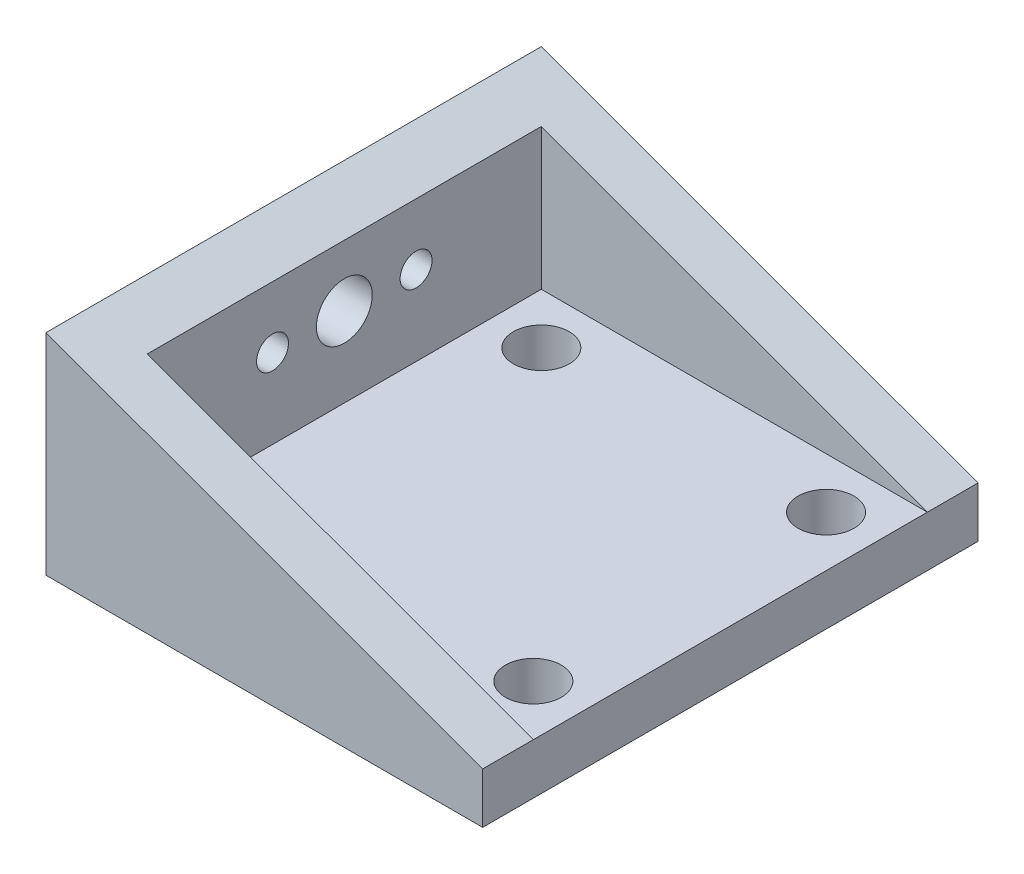
SolidWorks part; units mm, degrees
ref_plane "Front Plane" through (0, 0, 0) normal (0, 0, 1) x (1, 0, 0)
ref_plane "Top Plane" through (0, 0, 0) normal (0, 1, 0) x (1, 0, 0)
ref_plane "Right Plane" through (0, 0, 0) normal (1, 0, 0) x (0, 0, -1)
sketch "Sketch1" plane through (0, 0, 0) normal (0, 0, 1) x (1, 0, 0)
  line L0 (0, 0) -> (0, 13.175)
  line L1 (0, 13.175) -> (27.375, 3.175)
  line L2 (0, 0) -> (27.375, 0)
  line L5 (27.375, 3.175) -> (27.375, 0)
  point P2 (31.75, 0)
  point P3 (3.175, 0)
  dimension "D1" = 13.175
  dimension "D3" = 3.175
  dimension "D4" = 24.2
  dimension "D5" = 4.375
  dimension "D6" = 3.175
extrude "Boss-Extrude1" add sketch "Sketch1" along normal mid plane 31.05
sketch "Sketch2" plane through (0, 0, 0) normal (0, -1, 0) x (1, 0, 0)
  line L0 (27.375, 15.525) -> (27.375, -15.525) construction
  line L1 (3.175, 12.35) -> (27.375, 12.35)
  line L2 (3.175, 12.35) -> (3.175, -12.35)
  line L3 (3.175, -12.35) -> (27.375, -12.35)
  line L4 (27.375, 12.35) -> (27.375, -12.35)
  line L5 (0, 15.525) -> (27.375, 15.525) construction
  line L7 (27.375, 15.525) -> (27.375, 12.35) construction
  line L8 (27.375, -12.35) -> (27.375, -15.525) construction
  dimension "D1" = 3.175
extrude "Cut-Extrude1" cut sketch "Sketch2" against normal up to next from offset 3.175 offset against normal yes
sketch "Sketch4" plane through (0, 0, 0) normal (1, 0, 0) x (0, 0, -1)
  line L0 (0, 0) -> (0, 13.175) construction
  line L1 (4.5, 8.175) -> (-4.5, 8.175) construction
  circle A0 centre (0, 8.175) radius 1.75
  circle A1 centre (-4.5, 8.175) radius 1
  circle A2 centre (4.5, 8.175) radius 1
  dimension "D2" = 3.5
  dimension "D4" = 2
  dimension "D5" = 2
  dimension "D1" = 8.175
  dimension "D3" = 4.5
extrude "Cut-Extrude2" cut sketch "Sketch4" along normal up to next
sketch "Sketch5" plane through (0, 0, 0) normal (0, 1, 0) x (1, 0, 0)
  line L0 (3.175, -12.35) -> (27.375, -12.35) construction
  line L1 (3.175, -12.35) -> (3.175, 12.35) construction
  line L2 (3.175, 12.35) -> (27.375, 12.35) construction
  line L3 (27.375, -12.35) -> (27.375, 12.35) construction
  circle A0 centre (6.35, -9.175) radius 1.7526
  circle A1 centre (6.35, -9.175) radius 3.175 construction
  circle A2 centre (6.35, 9.175) radius 3.175 construction
  circle A3 centre (6.35, 9.175) radius 1.7526
  circle A4 centre (24.2, -9.175) radius 3.175 construction
  circle A5 centre (24.2, 9.175) radius 3.175 construction
  circle A6 centre (24.2, -9.175) radius 1.7526
  circle A7 centre (24.2, 9.175) radius 1.7526
  dimension "D1" = 3.5052
  dimension "D2" = 6.35
  dimension "D3" = 6.35
  dimension "D4" = 3.5052
extrude "Cut-Extrude3" cut sketch "Sketch5" along normal up to next
equation "\"D4@Sketch1\"=9mm + 15.2mm "
equation "\"D1@Sketch1\"=10mm + .125"
equation "\"D1@Boss-Extrude1\"=12mm + .25in + .5"
equation "\"D1@Sketch4\"=5mm + .125"
